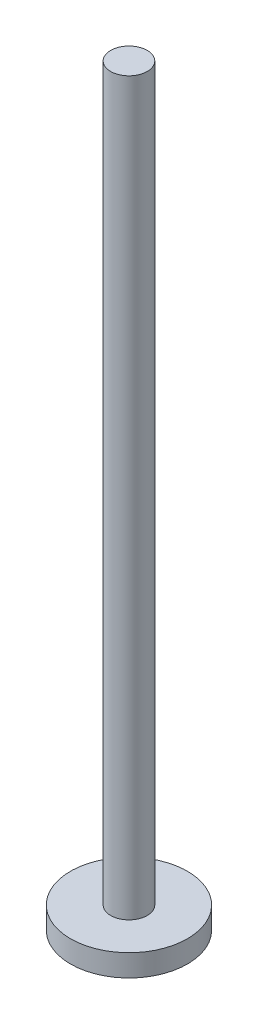
SolidWorks part; units mm, degrees
material "6061-T6 (SS)"
ref_plane "前视基准面" through (0, 0, 0) normal (0, 0, 1) x (1, 0, 0)
ref_plane "上视基准面" through (0, 0, 0) normal (0, 1, 0) x (1, 0, 0)
ref_plane "右视基准面" through (0, 0, 0) normal (1, 0, 0) x (0, 0, -1)
sketch "草图1" plane through (0, 0, 0) normal (0, 1, 0) x (1, 0, 0)
  circle A0 centre (0, 0) radius 8
  dimension "D1" = 16
extrude "凸台-拉伸1" add sketch "草图1" along normal blind 3
sketch "草图2" plane through (0, 3, 0) normal (0, 1, 0) x (1, 0, 0)
  circle A0 centre (0, 0) radius 2.5
  dimension "D1" = 5
extrude "凸台-拉伸2" add sketch "草图2" along normal blind 100
move or copy body "实体-移动/复制1" [suppressed] bodies to move or copy 106
equation "\"行程L\"= 50"
equation "\"D1@凸台-拉伸2\"=\"行程L\"+50"
